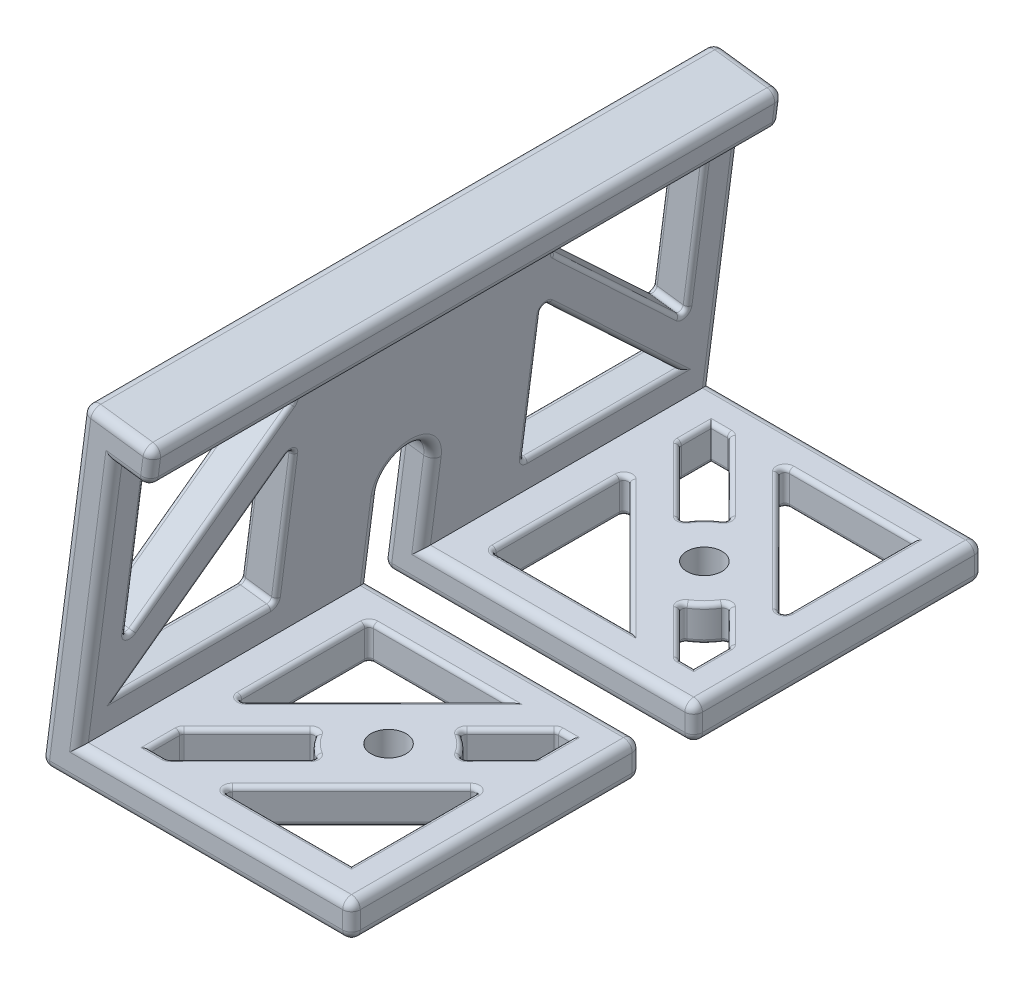
SolidWorks part; units mm, degrees
ref_plane "Plan de face" through (0, 0, 0) normal (0, 0, 1) x (1, 0, 0)
ref_plane "Plan de dessus" through (0, 0, 0) normal (0, 1, 0) x (1, 0, 0)
ref_plane "Plan de droite" through (0, 0, 0) normal (1, 0, 0) x (0, 0, -1)
sketch "Esquisse1" plane through (0, 0, 0) normal (0, 0, 1) x (1, 0, 0)
  line L0 (0, 0) -> (-35.5542, 0)
  line L1 (-35.5542, 0) -> (-33.4539, 16.141)
  line L2 (-30.5795, 38.2319) -> (-22.6463, 37.1996)
  line L3 (-22.6463, 37.1996) -> (-23.1625, 33.2331)
  line L4 (-23.1625, 33.2331) -> (-27.129, 33.7492)
  line L5 (-27.129, 33.7492) -> (-31, 4)
  line L6 (-31, 4) -> (0, 4)
  line L7 (0, 4) -> (0, 0)
  line L8 (-23.1625, 33.2331) -> (3.3548, 29.7827) construction
  line L9 (0, 4) -> (3.3548, 29.7827) construction
  line L10 (-32.6797, 22.0909) -> (-34.5355, 22.3323)
  line L11 (-33.4539, 16.141) -> (-35.3096, 16.3825)
  line L12 (-33.0668, 19.116) -> (-39.6117, 19.9676) construction
  line L13 (-32.6797, 22.0909) -> (-30.5795, 38.2319)
  line L14 (-33.4539, 16.141) -> (-32.6797, 22.0909) construction
  circle A0 centre (-39.6117, 19.9676) radius 1.6
  arc A1 (-34.5355, 22.3323) -> (-35.3096, 16.3825) centre (-39.6117, 19.9676) ccw
  point P20 (-34.0585, 19.245)
  dimension "D8" = 3.2
  dimension "D9" = 11.2
  dimension "D1" = 4
  dimension "D2" = 4
  dimension "D3" = 4
  dimension "D4" = 31
  dimension "D5" = 4
  dimension "D6" = 30
  dimension "D7" = 26
  dimension "D10" = 6
  dimension "D11" = 1
extrude "Boss.-Extru.1" add sketch "Esquisse1" along normal blind 72
sketch "Esquisse3" plane through (0, 4, 0) normal (0, 1, 0) x (1, 0, 0)
  line L0 (-13.78, -18) -> (-13.78, -54) construction
  line L1 (-31, -72) -> (-31, 0) construction
  line L2 (-31, -39) -> (0, -39)
  line L3 (0, -72) -> (0, 0) construction
  line L4 (0, -39) -> (0, -33)
  line L5 (0, -33) -> (-31, -33)
  line L6 (-31, -33) -> (-31, -39)
  line L7 (-27, -43) -> (-11.2653, -43)
  line L8 (-11.2653, -43) -> (-27, -58.7347)
  line L9 (-27, -58.7347) -> (-27, -43)
  line L10 (-4, -52.7053) -> (-19.2947, -68)
  line L11 (-19.2947, -68) -> (-4, -68)
  line L12 (-4, -68) -> (-4, -52.7053)
  line L13 (0, -72) -> (-31, -72) construction
  line L14 (-18.0226, -49.7574) -> (-15.1942, -52.5858) construction
  line L15 (-9.5374, -58.2426) -> (-12.3658, -55.4142) construction
  line L16 (-4, -43) -> (-4, -47.0484)
  line L17 (-4, -47.0484) -> (-8.3658, -51.4142)
  line L18 (-4, -43) -> (-5.6084, -43)
  line L19 (-5.6084, -43) -> (-11.1942, -48.5858)
  line L20 (-27, -68) -> (-24.9516, -68)
  line L21 (-24.9516, -68) -> (-16.3658, -59.4142)
  line L22 (-27, -68) -> (-27, -64.3916)
  line L23 (-27, -64.3916) -> (-19.1942, -56.5858)
  line L24 (-31, -36) -> (0, -36) construction
  line L25 (-4, -29) -> (-5.6084, -29)
  line L26 (-4, -29) -> (-4, -24.9516)
  line L27 (-4, -24.9516) -> (-8.3658, -20.5858)
  line L28 (-5.6084, -29) -> (-11.1942, -23.4142)
  line L29 (-19.2947, -4) -> (-4, -4)
  line L30 (-4, -19.2947) -> (-19.2947, -4)
  line L31 (-4, -4) -> (-4, -19.2947)
  line L32 (-27, -4) -> (-27, -7.6084)
  line L33 (-27, -4) -> (-24.9516, -4)
  line L34 (-24.9516, -4) -> (-16.3658, -12.5858)
  line L35 (-27, -7.6084) -> (-19.1942, -15.4142)
  line L36 (-11.2653, -29) -> (-27, -13.2653)
  line L37 (-27, -29) -> (-11.2653, -29)
  line L38 (-27, -13.2653) -> (-27, -29)
  circle A0 centre (-13.78, -18) radius 2
  circle A1 centre (-13.78, -54) radius 2
  arc A2 (-19.1942, -56.5858) -> (-16.3658, -59.4142) centre (-13.78, -54) ccw
  arc A3 (-8.3658, -51.4142) -> (-11.1942, -48.5858) centre (-13.78, -54) ccw
  arc A4 (-8.3658, -20.5858) -> (-11.1942, -23.4142) centre (-13.78, -18) cw
  arc A5 (-19.1942, -15.4142) -> (-16.3658, -12.5858) centre (-13.78, -18) cw
  point P6 (-31, -36)
  point P7 (-13.78, -36)
  point P12 (-31, -36)
  dimension "D1" = 4
  dimension "D2" = 36
  dimension "D3" = 17.22
  dimension "D4" = 6
  dimension "D5" = 4
  dimension "D6" = 4
  dimension "D7" = 4
  dimension "D8" = 4
  dimension "D9" = 4
  dimension "D10" = 4
  dimension "D11" = 4
  dimension "D12" = 4
  dimension "D13" = 4
extrude "Enlèv. mat.-Extru.1" cut sketch "Esquisse3" against normal through all
sketch "Esquisse4" plane through (2.2825, 17.5416, 0) normal (0.129, 0.9916, 0) x (0.9916, -0.129, 0)
  line L0 (-35.257, -72) -> (-35.257, 0) construction
  line L1 (-35.257, -25.875) -> (-48.457, -25.875)
  line L2 (-35.257, -25.875) -> (-35.257, 1)
  line L3 (-35.257, 1) -> (-48.457, 1)
  line L4 (-48.457, -25.875) -> (-48.457, 1)
  line L5 (-35.257, -72) -> (-35.257, 0) construction
  line L6 (-35.257, -29.875) -> (-48.457, -29.875)
  line L7 (-35.257, -29.875) -> (-35.257, -42.125)
  line L8 (-35.257, -42.125) -> (-48.457, -42.125)
  line L9 (-48.457, -29.875) -> (-48.457, -42.125)
  line L10 (-35.257, -46.125) -> (-48.457, -46.125)
  line L11 (-35.257, -46.125) -> (-35.257, -73)
  line L12 (-35.257, -73) -> (-48.457, -73)
  line L13 (-48.457, -46.125) -> (-48.457, -73)
  line L14 (-37.1283, 0) -> (-47.457, 0) construction
  line L15 (-47.457, -72) -> (-37.1283, -72) construction
  line L16 (-47.457, 0) -> (-47.457, -72) construction
  dimension "D1" = 4
  dimension "D2" = 4
  dimension "D3" = 1
  dimension "D4" = 1
  dimension "D5" = 1
  dimension "D6" = 20.25
extrude "Enlèv. mat.-Extru.2" cut sketch "Esquisse4" against normal through all and the other way through all
sketch "Esquisse5" plane through (-34.9622, 4.5493, 0) normal (-0.9916, 0.129, 0) x (0, 0, 1)
  line L8 (4, 25.9666) -> (21.875, 25.9666)
  line L9 (0, 33.9666) -> (0, -4.5876) construction
  line L10 (25.875, 20.2895) -> (25.875, 9.0895) construction
  line L11 (72, 33.9666) -> (0, 33.9666) construction
  line L12 (4, 3.4124) -> (21.875, 3.4124)
  line L13 (72, -4.5876) -> (0, -4.5876) construction
  line L14 (33, 9.4124) -> (33, -4.5876)
  line L15 (33, -4.5876) -> (39, -4.5876)
  line L16 (39, -4.5876) -> (39, 9.4124)
  line L17 (4, 25.9666) -> (4, 8.9371)
  line L18 (4, 8.9371) -> (21.875, 25.9666)
  line L19 (4, 3.4124) -> (21.875, 20.4419)
  line L20 (21.875, 20.4419) -> (21.875, 3.4124)
  line L21 (36, -4.5876) -> (36, 33.9666) construction
  line L22 (68, 3.4124) -> (50.125, 20.4419)
  line L23 (50.125, 20.4419) -> (50.125, 3.4124)
  line L24 (68, 3.4124) -> (50.125, 3.4124)
  line L25 (68, 25.9666) -> (68, 8.9371)
  line L26 (68, 8.9371) -> (50.125, 25.9666)
  line L27 (68, 25.9666) -> (50.125, 25.9666)
  arc A0 (39, 9.4124) -> (33, 9.4124) centre (36, 9.4124) ccw
  point P26 (36, -4.5876)
  dimension "D7" = 6
  dimension "D2" = 4
  dimension "D5" = 8
  dimension "D6" = 8
  dimension "D8" = 6
  dimension "D9" = 4
  dimension "D10" = 4
extrude "Enlèv. mat.-Extru.3" cut sketch "Esquisse5" against normal up to vertex
fillet "Congé1" radius 0.5 120 edges at (-4, 0, 26.9758) (-4, 4, 26.9758) (-25.9758, 0, 4) (-25.9758, 4, 4) (-11.6474, 0, 4) (-11.6474, 4, 4) (-4, 0, 11.6474) (-4, 4, 11.6474) (-9.5374, 0, 22.2426) (-9.5374, 4, 22.2426) (-4.8042, 0, 29) (-4.8042, 4, 29) (-27, 0, 5.8042) (-27, 4, 5.8042) (-18.0226, 0, 13.7574) (-18.0226, 4, 13.7574) (-19.1326, 0, 21.1326) (-19.1326, 4, 21.1326) (-19.1326, 0, 29) (-19.1326, 4, 29) (-4, 0, 45.0242) (-4, 4, 45.0242) (-4.8042, 0, 43) (-4.8042, 4, 43) (-9.5374, 0, 49.7574) (-9.5374, 4, 49.7574) (-4, 0, 60.3526) (-4, 4, 60.3526) (-11.6474, 0, 68) (-11.6474, 4, 68) (-25.9758, 0, 68) (-25.9758, 4, 68) (-18.0226, 0, 58.2426) (-18.0226, 4, 58.2426) (-27, 0, 66.1958) (-27, 4, 66.1958) (-19.1326, 0, 43) (-19.1326, 4, 43) (-19.1326, 0, 50.8674) (-19.1326, 4, 50.8674) (-29.4567, 15.8606, 59.0625) (-30.5554, 7.417, 59.0625) (-34.5219, 7.9331, 59.0625) (-33.4233, 16.3767, 59.0625) (-30.5554, 7.417, 12.9375) (-29.4567, 15.8606, 12.9375) (-33.4233, 16.3767, 12.9375) (-34.5219, 7.9331, 12.9375) (-28.7438, 21.3391, 4) (-27.6452, 29.7827, 12.9375) (-31.6117, 30.2988, 12.9375) (-32.7104, 21.8552, 4) (-27.6452, 29.7827, 59.0625) (-28.7438, 21.3391, 68) (-32.7104, 21.8552, 68) (-31.6117, 30.2988, 59.0625) (-4, 2, 24.9516) (-6.1829, 0, 22.7687) (-8.3658, 2, 20.5858) (-6.1829, 4, 22.7687) (-16.3658, 2, 12.5858) (-20.6587, 0, 8.2929) (-24.9516, 2, 4) (-20.6587, 4, 8.2929) (-19.2947, 2, 4) (-11.6474, 0, 11.6474) (-4, 2, 19.2947) (-11.6474, 4, 11.6474) (-11.1942, 2, 23.4142) (-8.4013, 0, 26.2071) (-5.6084, 2, 29) (-8.4013, 4, 26.2071) (-27, 2, 7.6084) (-23.0971, 0, 11.5113) (-19.1942, 2, 15.4142) (-23.0971, 4, 11.5113) (-27, 2, 13.2653) (-27, 0, 21.1326) (-27, 2, 29) (-27, 4, 21.1326) (-8.3658, 2, 51.4142) (-6.1829, 0, 49.2313) (-4, 2, 47.0484) (-6.1829, 4, 49.2313) (-5.6084, 2, 43) (-8.4013, 0, 45.7929) (-11.1942, 2, 48.5858) (-8.4013, 4, 45.7929) (-4, 2, 52.7053) (-11.6474, 0, 60.3526) (-19.2947, 2, 68) (-11.6474, 4, 60.3526) (-24.9516, 2, 68) (-20.6587, 0, 63.7071) (-16.3658, 2, 59.4142) (-20.6587, 4, 63.7071) (-19.1942, 2, 56.5858) (-23.0971, 0, 60.4887) (-27, 2, 64.3916) (-23.0971, 4, 60.4887) (-27, 2, 43) (-27, 0, 50.8674) (-27, 2, 58.7347) (-27, 4, 50.8674) (-29.4567, 15.8606, 50.125) (-32.5387, 7.6751, 50.125) (-33.4233, 16.3767, 50.125) (-30.3413, 24.5622, 50.125) (-29.4567, 15.8606, 21.875) (-30.3413, 24.5622, 21.875) (-33.4233, 16.3767, 21.875) (-32.5387, 7.6751, 21.875) (-28.7438, 21.3391, 12.9375) (-29.6284, 30.0407, 21.875) (-32.7104, 21.8552, 12.9375) (-31.8258, 13.1536, 4) (-28.7438, 21.3391, 59.0625) (-31.8258, 13.1536, 68) (-32.7104, 21.8552, 59.0625) (-29.6284, 30.0407, 50.125)
fillet "Congé2" radius 1 37 edges at (-33.3607, 16.8579, 36) (-29.3941, 16.3418, 36) (-23.1625, 33.2331, 36) (-22.6463, 37.1996, 36) (-30.5795, 38.2319, 36) (-17.7771, 0, 0) (-15.5, 4, 0) (-29.0645, 18.8746, 0) (-25.1458, 33.4911, 0) (-22.9044, 35.2164, 0) (-26.6129, 37.7158, 0) (-33.0668, 19.116, 0) (-26.6129, 37.7158, 72) (-22.9044, 35.2164, 72) (-25.1458, 33.4911, 72) (-29.0645, 18.8746, 72) (-15.5, 4, 72) (-17.7771, 0, 72) (-33.0668, 19.116, 72) (0, 2, 0) (0, 0, 16.5) (0, 4, 16.5) (0, 2, 72) (0, 4, 55.5) (0, 0, 55.5) (-30.3906, 8.6834, 39) (-34.651, 6.9415, 39) (-17.7771, 0, 39) (0, 2, 39) (-15.5, 4, 39) (0, 2, 33) (-17.7771, 0, 33) (-34.651, 6.9415, 33) (-30.3906, 8.6834, 33) (-15.5, 4, 33) (-35.5542, 0, 55.5) (-35.5542, 0, 16.5)
